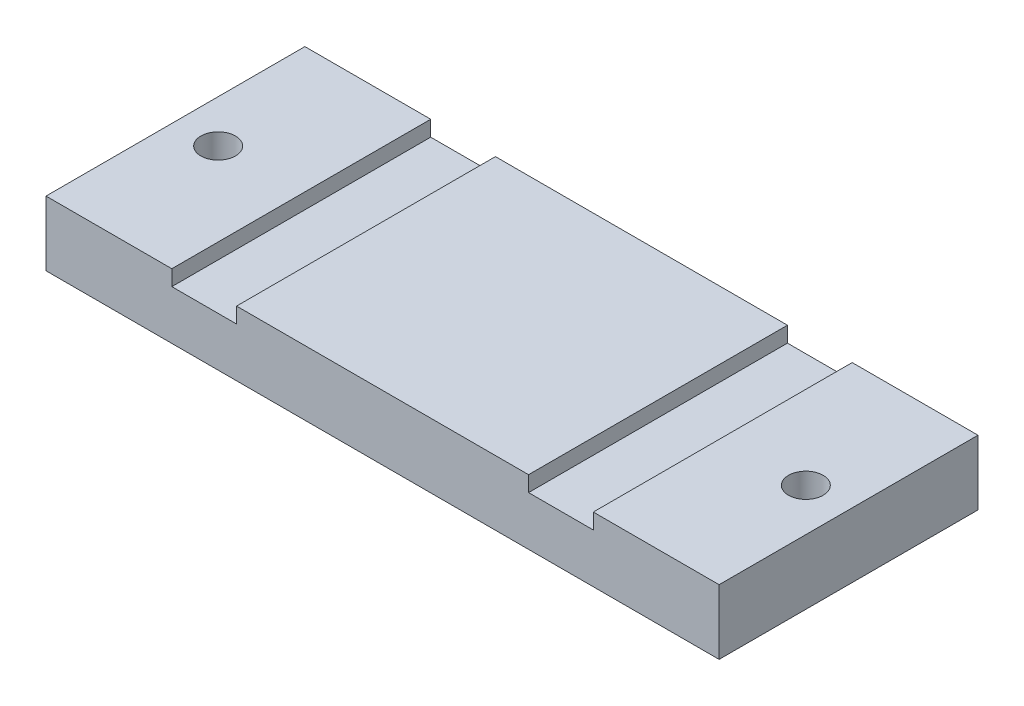
SolidWorks part; units mm, degrees
material "Delrin 2700 NC010, Low Viscosity Acetal Copolymer (SS)"
ref_plane "Front Plane" through (0, 0, 0) normal (0, 0, 1) x (1, 0, 0)
ref_plane "Top Plane" through (0, 0, 0) normal (0, 1, 0) x (1, 0, 0)
ref_plane "Right Plane" through (0, 0, 0) normal (1, 0, 0) x (0, 0, -1)
sketch "Sketch1" plane through (0, 0, 0) normal (0, 1, 0) x (1, 0, 0)
  line L1 (0, 0) -> (66.04, 0)
  line L2 (0, 0) -> (0, 25.4)
  line L3 (0, 25.4) -> (66.04, 25.4)
  line L4 (66.04, 0) -> (66.04, 25.4)
  dimension "D1" = 66.04
  dimension "D2" = 25.4
extrude "Boss-Extrude1" add sketch "Sketch1" along normal blind 6.35
hole_wizard "M3 Clearance Hole1" positions "Sketch4" profile "Sketch3" hole size "M3" standard "ANSI Metric" end condition through all
sketch "Sketch4" plane through (0, 6.35, 0) normal (0, 1, 0) x (1, 0, 0)
  line L0 (0, 12.7) -> (66.04, 12.7) construction
  line L1 (0, 25.4) -> (0, 0) construction
  line L2 (66.04, 0) -> (66.04, 25.4) construction
  line L4 (33.02, 0) -> (33.02, 25.4) construction
  line L5 (0, 0) -> (66.04, 0) construction
  line L6 (66.04, 25.4) -> (0, 25.4) construction
  point P0 (4.191, 12.7)
  point P2 (61.849, 12.7)
  dimension "D1" = 28.829
  dimension "D2" = 28.829
sketch "Sketch3" plane through (4.191, 6.35, -12.7) normal (1, 0, 0) x (0, 0, 1)
  line L0 (0, 0) -> (0, 6.35)
  line L1 (0, 6.35) -> (1.7, 6.35)
  line L2 (1.7, 6.35) -> (1.7, 0)
  line L5 (1.7, 0) -> (0, 0)
  line L11 (0, -6.35) -> (0, 107.95) construction
  dimension "Thru Hole Dia." = 3.4
  dimension "Thru Hole Depth" = 6.35
sketch "Sketch5" plane through (0, 0, 0) normal (0, 0, 1) x (1, 0, 0)
  line L0 (33.02, 6.35) -> (33.02, 0) construction
  line L5 (0, 6.35) -> (66.04, 6.35) construction
  line L6 (0, 0) -> (66.04, 0) construction
  line L7 (53.695, 4.826) -> (47.345, 4.826)
  line L8 (12.345, 6.35) -> (18.695, 6.35)
  line L9 (12.345, 6.35) -> (12.345, 4.826)
  line L10 (12.345, 4.826) -> (18.695, 4.826)
  line L11 (18.695, 6.35) -> (18.695, 4.826)
  line L12 (47.345, 6.35) -> (47.345, 4.826)
  line L13 (53.695, 6.35) -> (47.345, 6.35)
  line L14 (53.695, 6.35) -> (53.695, 4.826)
  point P11 (15.52, 4.826)
  dimension "D1" = 6.35
  dimension "D2" = 17.5
  dimension "D3" = 1.524
extrude "Cut-Extrude1" cut sketch "Sketch5" against normal through all
equation "\"spool lenght\"= 45mm"
equation "\"hole distance\"= 0.25in"
equation "\"D2@Sketch4\"=\"spool lenght\"/2 + \"hole distance\""
equation "\"D1@Sketch4\"=\"spool lenght\"/2 + \"hole distance\""
equation "\"tooth clearance\"= 1.5mm"
equation "\"D3@Sketch5\"=\"tooth clearance\""
